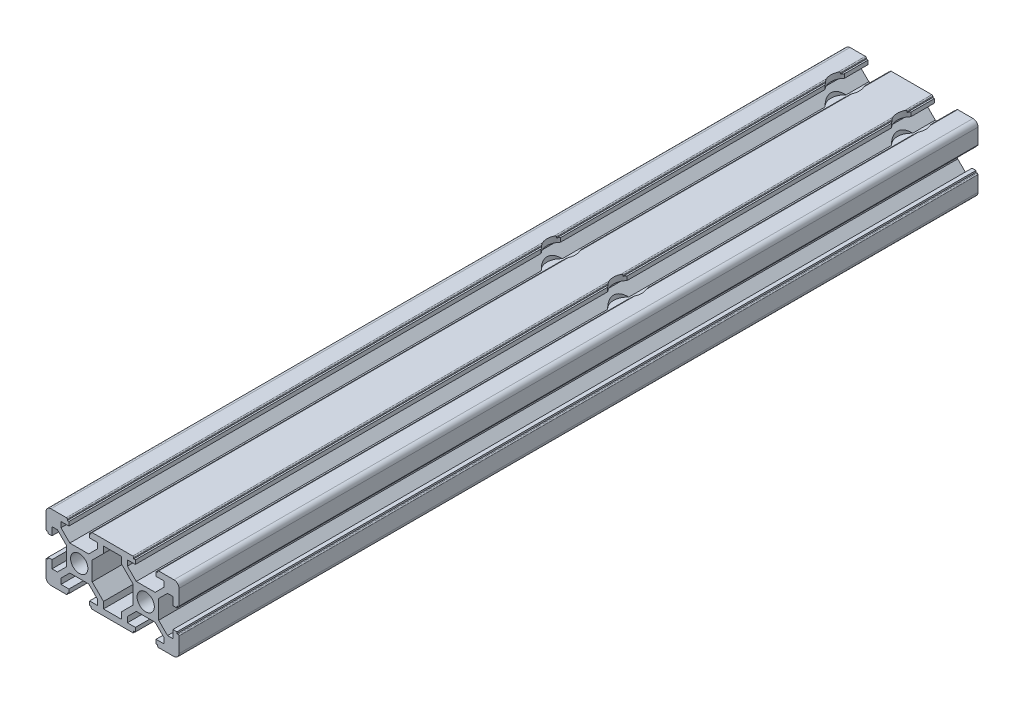
SolidWorks part; units mm, degrees
ref_plane "前视基准面" through (0, 0, 0) normal (0, 0, 1) x (1, 0, 0)
ref_plane "上视基准面" through (0, 0, 0) normal (0, 1, 0) x (1, 0, 0)
ref_plane "右视基准面" through (0, 0, 0) normal (1, 0, 0) x (0, 0, -1)
sketch "草图1" plane through (0, 0, 0) normal (0, 0, 1) x (1, 0, 0)
  line L0 (0, 0) -> (0, -41497.3383) construction
  line L1 (0, 0) -> (41497.3383, 0) construction
  line L2 (-13.9, 0) -> (-13.9, 2.8393)
  line L3 (-13.9, 2.8393) -> (-16.5607, 5.5)
  line L4 (-16.5607, 5.5) -> (-18.2, 5.5)
  line L5 (-18.2, 5.5) -> (-18.2, 3.1)
  line L6 (-18.2, 3.1) -> (-19.4, 3.1)
  line L7 (-19.4, 3.1) -> (-19.4, 3.6)
  line L8 (-19.4, 3.6) -> (-20, 3.6)
  line L9 (-20, 3.6) -> (-20, 10)
  line L10 (-20, 10) -> (-13.6, 10)
  line L11 (-13.6, 10) -> (-13.6, 9.4)
  line L12 (-13.6, 9.4) -> (-13.1, 9.4)
  line L13 (-13.1, 9.4) -> (-13.1, 8.2)
  line L14 (-13.1, 8.2) -> (-15.5, 8.2)
  line L15 (-15.5, 6.5607) -> (-12.8393, 3.9)
  line L16 (-12.8393, 3.9) -> (-7.1607, 3.9)
  line L17 (-4.5, 6.5607) -> (-7.1607, 3.9)
  line L18 (-4.5, 6.5607) -> (-4.5, 8.2)
  line L19 (-4.5, 8.2) -> (-6.9, 8.2)
  line L20 (-6.9, 8.2) -> (-6.9, 9.4)
  line L21 (-6.9, 9.4) -> (-6.4, 9.4)
  line L22 (-6.4, 9.4) -> (-6.4, 10)
  line L23 (-6.4, 10) -> (6.4, 10)
  line L24 (-15.5, 8.2) -> (-15.5, 6.5607)
  line L25 (-10, 0) -> (-20, 10) construction
  line L26 (-6.1, -2.8393) -> (-6.1, 2.8393)
  line L27 (-6.1, 2.8393) -> (-2.7, 6.2393)
  line L28 (-2.7, 6.2393) -> (-2.7, 8.2)
  line L29 (-2.7, 8.2) -> (2.7, 8.2)
  line L30 (-10, 0) -> (0, 10) construction
  line L31 (13.9, 0) -> (13.9, 2.8393)
  line L32 (6.1, -2.8393) -> (6.1, 2.8393)
  line L33 (4.5, 6.5607) -> (7.1607, 3.9)
  line L34 (12.8393, 3.9) -> (7.1607, 3.9)
  line L35 (6.1, 2.8393) -> (2.7, 6.2393)
  line L36 (2.7, 6.2393) -> (2.7, 8.2)
  line L37 (4.5, 6.5607) -> (4.5, 8.2)
  line L38 (6.4, 9.4) -> (6.4, 10)
  line L39 (6.9, 9.4) -> (6.4, 9.4)
  line L40 (6.9, 8.2) -> (6.9, 9.4)
  line L41 (4.5, 8.2) -> (6.9, 8.2)
  line L42 (13.1, 9.4) -> (13.1, 8.2)
  line L43 (13.6, 9.4) -> (13.1, 9.4)
  line L44 (13.6, 10) -> (13.6, 9.4)
  line L45 (20, 10) -> (13.6, 10)
  line L46 (20, 3.6) -> (20, 10)
  line L47 (19.4, 3.6) -> (20, 3.6)
  line L48 (19.4, 3.1) -> (19.4, 3.6)
  line L49 (18.2, 3.1) -> (19.4, 3.1)
  line L50 (18.2, 5.5) -> (18.2, 3.1)
  line L51 (16.5607, 5.5) -> (18.2, 5.5)
  line L52 (13.9, 2.8393) -> (16.5607, 5.5)
  line L53 (15.5, 6.5607) -> (12.8393, 3.9)
  line L54 (15.5, 8.2) -> (15.5, 6.5607)
  line L55 (13.1, 8.2) -> (15.5, 8.2)
  line L56 (15.5, -6.5607) -> (12.8393, -3.9)
  line L57 (13.9, -2.8393) -> (16.5607, -5.5)
  line L58 (16.5607, -5.5) -> (18.2, -5.5)
  line L59 (18.2, -5.5) -> (18.2, -3.1)
  line L60 (18.2, -3.1) -> (19.4, -3.1)
  line L61 (19.4, -3.1) -> (19.4, -3.6)
  line L62 (19.4, -3.6) -> (20, -3.6)
  line L63 (12.8393, -3.9) -> (7.1607, -3.9)
  line L64 (13.9, 0) -> (13.9, -2.8393)
  line L65 (13.1, -8.2) -> (15.5, -8.2)
  line L66 (15.5, -8.2) -> (15.5, -6.5607)
  line L67 (20, -3.6) -> (20, -10)
  line L68 (20, -10) -> (13.6, -10)
  line L69 (13.6, -10) -> (13.6, -9.4)
  line L70 (13.6, -9.4) -> (13.1, -9.4)
  line L71 (13.1, -9.4) -> (13.1, -8.2)
  line L72 (4.5, -8.2) -> (6.9, -8.2)
  line L73 (6.9, -8.2) -> (6.9, -9.4)
  line L74 (6.9, -9.4) -> (6.4, -9.4)
  line L75 (6.4, -9.4) -> (6.4, -10)
  line L76 (4.5, -6.5607) -> (4.5, -8.2)
  line L77 (2.7, -6.2393) -> (2.7, -8.2)
  line L78 (6.1, -2.8393) -> (2.7, -6.2393)
  line L79 (4.5, -6.5607) -> (7.1607, -3.9)
  line L80 (-2.7, -8.2) -> (2.7, -8.2)
  line L81 (-2.7, -6.2393) -> (-2.7, -8.2)
  line L82 (-6.1, -2.8393) -> (-2.7, -6.2393)
  line L83 (-4.5, -6.5607) -> (-7.1607, -3.9)
  line L84 (-4.5, -8.2) -> (-6.9, -8.2)
  line L85 (-4.5, -6.5607) -> (-4.5, -8.2)
  line L86 (-6.4, -10) -> (6.4, -10)
  line L87 (-6.4, -9.4) -> (-6.4, -10)
  line L88 (-6.9, -9.4) -> (-6.4, -9.4)
  line L89 (-6.9, -8.2) -> (-6.9, -9.4)
  line L90 (-13.1, -9.4) -> (-13.1, -8.2)
  line L91 (-13.6, -9.4) -> (-13.1, -9.4)
  line L92 (-13.6, -10) -> (-13.6, -9.4)
  line L93 (-15.5, -8.2) -> (-15.5, -6.5607)
  line L94 (-13.1, -8.2) -> (-15.5, -8.2)
  line L95 (-12.8393, -3.9) -> (-7.1607, -3.9)
  line L96 (-15.5, -6.5607) -> (-12.8393, -3.9)
  line L97 (-13.9, 0) -> (-13.9, -2.8393)
  line L98 (-13.9, -2.8393) -> (-16.5607, -5.5)
  line L99 (-19.4, -3.6) -> (-20, -3.6)
  line L100 (-19.4, -3.1) -> (-19.4, -3.6)
  line L101 (-18.2, -3.1) -> (-19.4, -3.1)
  line L102 (-18.2, -5.5) -> (-18.2, -3.1)
  line L103 (-16.5607, -5.5) -> (-18.2, -5.5)
  line L104 (-20, -3.6) -> (-20, -10)
  line L105 (-20, -10) -> (-13.6, -10)
  circle A0 centre (-10, 0) radius 2.6
  circle A1 centre (10, 0) radius 2.6
  point P50 (0, 8.2)
  point P95 (6.1, 0)
  point P96 (-6.1, 0)
  dimension "D1" = 5.2
  dimension "D2" = 45
  dimension "D3" = 1.5
  dimension "D4" = 20
  dimension "D5" = 40
  dimension "D6" = 0.75
  dimension "D7" = 7.2
  dimension "D8" = 6.2
  dimension "D9" = 6.1
  dimension "D10" = 1.8
  dimension "D11" = 1.2
  dimension "D12" = 12.2
  dimension "D13" = 5.4
  dimension "D14" = 11
  dimension "D15" = 1.5
  dimension "D16" = 0.75
extrude "凸台-拉伸1" add sketch "草图1" along normal mid plane 240.4
fillet "圆角1" radius 1.5 4 edges at (20, -10, 0) (20, 10, 0) (-20, -10, 0) (-20, 10, 0)
fillet "圆角2" radius 0.3 12 edges at (-6.4, 10, 0) (-13.6, 10, 0) (-20, 3.6, 0) (-20, -3.6, 0) (-13.6, -10, 0) (-6.4, -10, 0) (6.4, -10, 0) (20, -3.6, 0) (20, 3.6, 0) (13.6, -10, 0) (13.6, 10, 0) (6.4, 10, 0)
sketch "草图3" plane through (0, -3.9, 0) normal (0, -1, 0) x (1, 0, 0)
  line L0 (-10, -110.2) -> (10, -110.2) construction
  line L1 (-10, -24.8) -> (10, -24.8) construction
  line L2 (-6.1, -120.2) -> (6.1, -120.2) construction
  circle A0 centre (-10, -110.2) radius 2.1
  circle A1 centre (10, -110.2) radius 2.1
  circle A4 centre (-10, -24.8) radius 2.1
  circle A5 centre (10, -24.8) radius 2.1
  point P5 (0, -110.2)
  point P18 (0, -24.8)
  dimension "D1" = 4.2
  dimension "D2" = 20
  dimension "D4" = 85.4
  dimension "D3" = 10
extrude "切除-拉伸1" cut sketch "草图3" against normal through all both and the other way through all
sketch "草图4" plane through (0, 3.9, 0) normal (0, 1, 0) x (1, 0, 0)
  circle A2 centre (-10, 110.2) radius 4.25
  circle A3 centre (10, 110.2) radius 4.25
  circle A4 centre (-10, 24.8) radius 4.25
  circle A5 centre (10, 24.8) radius 4.25
  dimension "D1" = 8.5
extrude "切除-拉伸2" cut sketch "草图4" along normal through all
equation "\"D6@草图1\"=1/2*\"D3@草图1\""
equation "\"D16@草图1\"=0.5*\"D15@草图1\""
